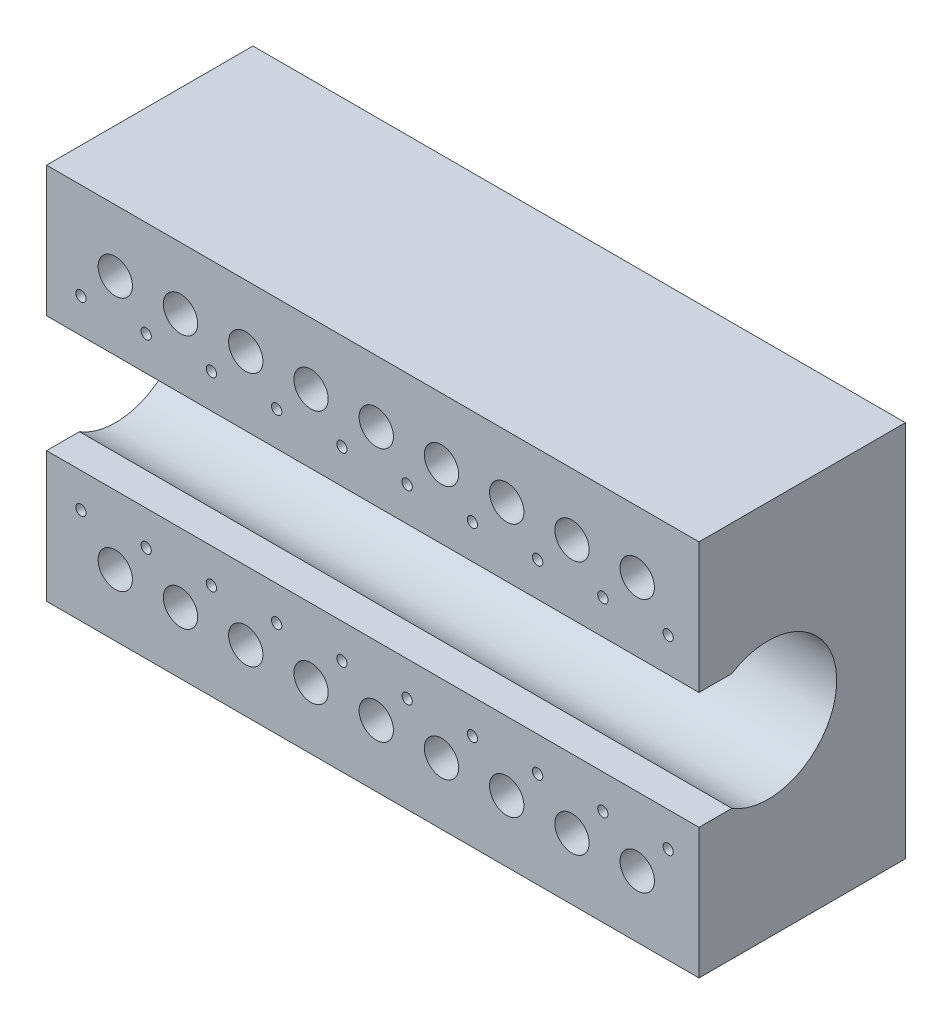
SolidWorks part; units mm, degrees
ref_plane "Front Plane" through (0, 0, 0) normal (0, 0, 1) x (1, 0, 0)
ref_plane "Top Plane" through (0, 0, 0) normal (0, 1, 0) x (1, 0, 0)
ref_plane "Right Plane" through (0, 0, 0) normal (1, 0, 0) x (0, 0, -1)
sketch "Sketch1" plane through (0, 0, 0) normal (1, 0, 0) x (0, 0, -1)
  line L1 (0, 0) -> (601, 0)
  line L2 (0, 0) -> (0, 1100)
  line L3 (0, 1100) -> (601, 1100)
  line L4 (601, 0) -> (601, 1100)
  circle A0 centre (201, 550) radius 200
  dimension "D3" = 400
  dimension "D5" = 400
  dimension "D1" = 1100
  dimension "D2" = 601
  dimension "D4" = 550
extrude "Boss-Extrude1" add sketch "Sketch1" along normal blind 1900
sketch "Sketch2" plane through (0, 0, 0) normal (0, 0, 1) x (1, 0, 0)
  line L0 (0, 1100) -> (0, 0) construction
  line L1 (0, 720) -> (1900, 720)
  line L2 (0, 720) -> (0, 380)
  line L3 (0, 380) -> (1900, 380)
  line L4 (1900, 720) -> (1900, 380)
  line L5 (1900, 1100) -> (0, 1100) construction
  dimension "D1" = 340
  dimension "D2" = 1900
  dimension "D3" = 0
  dimension "D4" = 380
extrude "Cut-Extrude1" cut sketch "Sketch2" against normal blind 300
sketch "Sketch3" plane through (0, 0, 0) normal (0, 0, 1) x (1, 0, 0)
  line L0 (1900, 720) -> (0, 720) construction
  line L1 (0, 1100) -> (0, 720) construction
  circle A0 centre (100, 820) radius 15
  circle A1 centre (200, 920) radius 50
  circle A2 centre (290, 820) radius 15
  circle A3 centre (480, 820) radius 15
  circle A4 centre (670, 820) radius 15
  circle A5 centre (860, 820) radius 15
  circle A6 centre (1050, 820) radius 15
  circle A7 centre (1240, 820) radius 15
  circle A8 centre (1430, 820) radius 15
  circle A9 centre (1620, 820) radius 15
  circle A10 centre (1810, 820) radius 15
  circle A11 centre (290, 280) radius 15
  circle A12 centre (480, 280) radius 15
  circle A13 centre (670, 280) radius 15
  circle A14 centre (860, 280) radius 15
  circle A15 centre (1050, 280) radius 15
  circle A16 centre (1240, 280) radius 15
  circle A17 centre (1430, 280) radius 15
  circle A18 centre (1620, 280) radius 15
  circle A19 centre (1810, 280) radius 15
  circle A20 centre (100, 280) radius 15
  circle A21 centre (390, 920) radius 50
  circle A22 centre (580, 920) radius 50
  circle A23 centre (770, 920) radius 50
  circle A24 centre (960, 920) radius 50
  circle A25 centre (1150, 920) radius 50
  circle A26 centre (1340, 920) radius 50
  circle A27 centre (1530, 920) radius 50
  circle A28 centre (1720, 920) radius 50
  circle A29 centre (390, 180) radius 50
  circle A30 centre (580, 180) radius 50
  circle A31 centre (770, 180) radius 50
  circle A32 centre (960, 180) radius 50
  circle A33 centre (1150, 180) radius 50
  circle A34 centre (1340, 180) radius 50
  circle A35 centre (1530, 180) radius 50
  circle A36 centre (1720, 180) radius 50
  circle A37 centre (200, 180) radius 50
  dimension "D2" = 30
  dimension "D3" = 100
  dimension "D8" = 100
  dimension "D9" = 9
  dimension "D1" = 100
  dimension "D4" = 200
  dimension "D5" = 200
  dimension "D6" = 10
  dimension "D7" = 2
  dimension "D10" = 2
extrude "Cut-Extrude2" cut sketch "Sketch3" against normal through all
